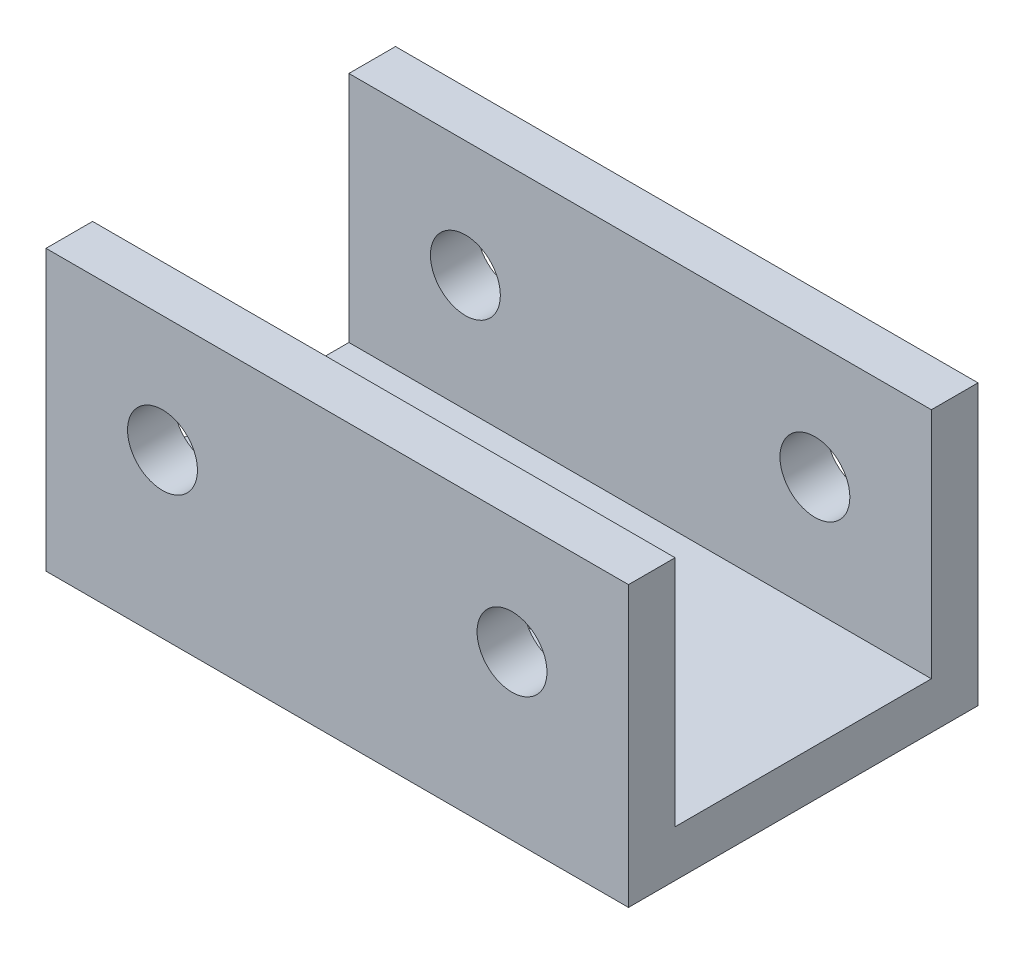
SolidWorks part; units mm, degrees
ref_plane "前视基准面" through (0, 0, 0) normal (0, 0, 1) x (1, 0, 0)
ref_plane "上视基准面" through (0, 0, 0) normal (0, 1, 0) x (1, 0, 0)
ref_plane "右视基准面" through (0, 0, 0) normal (1, 0, 0) x (0, 0, -1)
sketch "草图1" plane through (0, 0, 0) normal (0, 1, 0) x (1, 0, 0)
  line L0 (-50, 30) -> (50, 30)
  line L1 (50, 30) -> (50, -30)
  line L2 (50, -30) -> (-50, -30)
  line L3 (-50, -30) -> (-50, 30)
extrude "凸台-拉伸1" add sketch "草图1" along normal blind 48
ref_plane "基准面1" through (0, 48, 0) normal (0, 1, 0) x (1, 0, 0)
sketch "草图2" plane through (0, 48, 0) normal (0, 1, 0) x (1, 0, 0)
  line L0 (-52, 22) -> (52, 22)
  line L1 (52, 22) -> (52, -22)
  line L2 (52, -22) -> (-52, -22)
  line L3 (-52, -22) -> (-52, 22)
extrude "切除-拉伸1" cut sketch "草图2" against normal blind 40
sketch "草图3" plane through (0, 0, 0) normal (0, 1, 0) x (1, 0, 0)
  line L0 (-15, 5) -> (15, 5)
  line L1 (15, -5) -> (-15, -5)
  arc A0 (15, 5) -> (15, -5) centre (15, 0) cw
  arc A1 (-15, -5) -> (-15, 5) centre (-15, 0) cw
extrude "切除-拉伸2" cut sketch "草图3" along normal through all
ref_plane "基准面2" through (0, 0, 30) normal (0, 0, 1) x (1, 0, 0)
sketch "草图4" plane through (0, 0, 30) normal (0, 0, 1) x (1, 0, 0)
  circle A0 centre (-30, 28) radius 6
  circle A1 centre (30, 28) radius 6
extrude "切除-拉伸3" cut sketch "草图4" against normal mid plane 202
